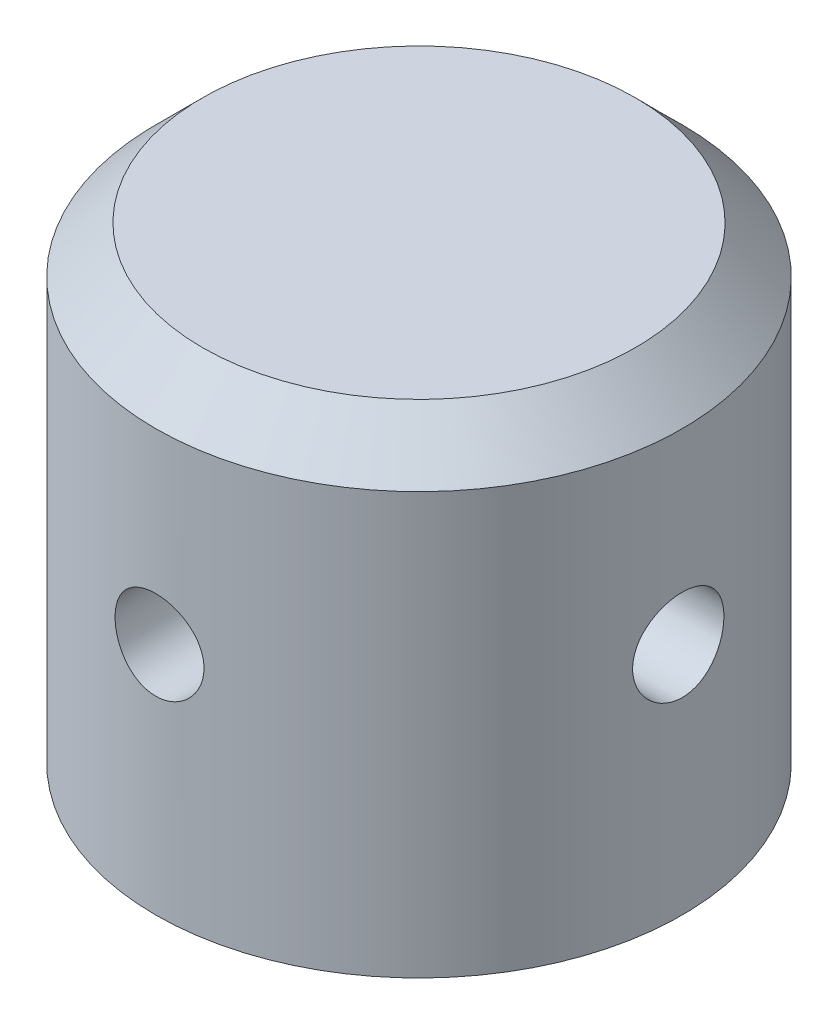
SolidWorks part; units mm, degrees
ref_plane "Front Plane" through (0, 0, 0) normal (0, 0, 1) x (1, 0, 0)
ref_plane "Top Plane" through (0, 0, 0) normal (0, 1, 0) x (1, 0, 0)
ref_plane "Right Plane" through (0, 0, 0) normal (1, 0, 0) x (0, 0, -1)
sketch "Sketch1" plane through (0, 0, 0) normal (0, 1, 0) x (1, 0, 0)
  circle A0 centre (0, 0) radius 14.2875
  dimension "D1" = 28.575
extrude "Boss-Extrude1" add sketch "Sketch1" along normal blind 25.4
sketch "Sketch2" plane through (0, 0, 0) normal (0, -1, 0) x (-1, 0, 0)
  circle A0 centre (0, 0) radius 3.302
  dimension ".28" = 6.604
extrude "Cut-Extrude1" cut sketch "Sketch2" against normal blind 8
sketch "Sketch3" plane through (0, 0, 0) normal (1, 0, 0) x (0, 0, -1)
  line L0 (0, 0) -> (0, 12.7) construction
  line L1 (0, 13.97) -> (0, -13.97) construction
  circle A0 centre (0, 12.7) radius 2.4765
  dimension "D2" = 4.953
  dimension "D1" = 12.7
extrude "Cut-Extrude2" cut sketch "Sketch3" against normal through all and the other way through all
chamfer "Chamfer1" distance 2.54 angle 45 1 edges at (0, 25.4, 14.2875)
sketch "Sketch4" plane through (0, 0, 0) normal (0, 0, 1) x (1, 0, 0)
  line L0 (0, 0) -> (0, 12.7) construction
  line L1 (0, -13.97) -> (0, 13.97) construction
  circle A0 centre (0, 12.7) radius 2.413
  dimension "D2" = 4.826
  dimension "D1" = 12.7
extrude "Cut-Extrude3" cut sketch "Sketch4" against normal through all and the other way through all
